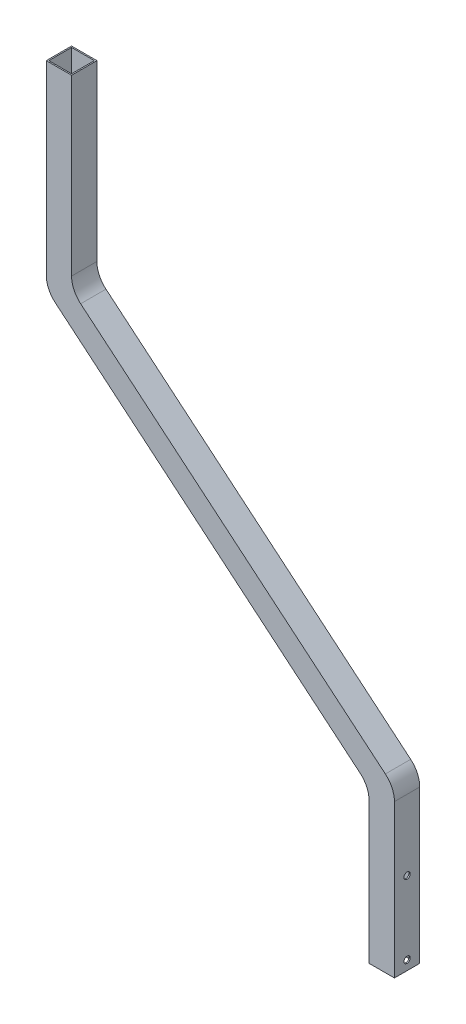
SolidWorks part; units mm, degrees
material "Alloy Steel"
ref_plane "Front Plane" through (0, 0, 0) normal (0, 0, 1) x (1, 0, 0)
ref_plane "Top Plane" through (0, 0, 0) normal (0, 1, 0) x (1, 0, 0)
ref_plane "Right Plane" through (0, 0, 0) normal (1, 0, 0) x (0, 0, -1)
sketch "Sketch1" plane through (0, 0, 0) normal (0, 0, 1) x (1, 0, 0)
  line L0 (0, 0) -> (-698.5, 0) construction
  line L1 (0, 0) -> (0, 1244.6) construction
  line L21 (0, 0) -> (0, 330.2)
  line L22 (0, 330.2) -> (-647.7, 871.9127)
  line L23 (-647.7, 1244.6) -> (-698.5, 1244.6)
  line L24 (-50.8, 0) -> (-50.8, 306.4618)
  line L25 (-50.8, 306.4618) -> (-698.5, 848.1746)
  line L26 (-50.8, 306.4618) -> (-749.3, 890.6618) construction
  line L27 (-647.7, 871.9127) -> (-647.7, 1244.6)
  line L28 (-698.5, 848.1746) -> (-698.5, 1244.6)
  line L29 (-749.3, 890.6618) -> (-749.3, 1244.6) construction
  line L30 (-50.8, 0) -> (0, 0)
  line L31 (-698.5, 914.4) -> (-698.5, 1244.6) construction
  line L32 (0, 330.2) -> (-698.5, 914.4) construction
  dimension "D1" = 698.5
  dimension "D2" = 1244.6
  dimension "D3" = 330.2
  dimension "D4" = 50.8
  dimension "D5" = 50.8
extrude "Boss-Extrude1" add sketch "Sketch1" along normal blind 50.8
fillet "Fillet1" radius 50.8 4 edges at (-50.8, 306.4618, 25.4) (0, 330.2, 25.4) (-647.7, 871.9127, 25.4) (-698.5, 848.1746, 25.4)
shell "Shell1" thickness 2.54
sketch "Sketch2" plane through (0, 0, 0) normal (0, -1, 0) x (1, 0, 0)
  line L0 (-2.54, 48.26) -> (-48.26, 48.26)
  line L5 (-48.26, 2.54) -> (-48.26, 48.26)
  line L6 (-2.54, 2.54) -> (-48.26, 2.54)
  line L7 (-2.54, 2.54) -> (-2.54, 48.26)
extrude "Cut-Extrude1" cut sketch "Sketch2" against normal blind 50.8
hole_wizard "#97 (0.5) Diameter Hole1" positions "3DSketch1" profile "Sketch3" hole size "#97" standard "ANSI Inch" end condition through all
sketch3d "3DSketch1"
  line L0 (0, 0, 50.8) -> (0, 306.4618, 50.8) construction
  line L1 (0, 0, 50.8) -> (0, 0, 0) construction
  point P0 (0, 19.05, 25.4)
  point P2 (0, 165.1, 25.4)
  dimension "D1" = 25.4
  dimension "D2" = 25.4
  dimension "D3" = 19.05
  dimension "D4" = 146.05
sketch "Sketch3" plane through (0, 19.05, 25.4) normal (0, 1, 0) x (0, 0, -1)
  line L0 (0, 0) -> (0, 698.5)
  line L1 (0, 698.5) -> (6.35, 698.5)
  line L2 (6.35, 698.5) -> (6.35, 0)
  line L5 (6.35, 0) -> (0, 0)
  line L11 (0, -6.35) -> (0, 107.95) construction
  dimension "Thru Hole Dia." = 12.7
  dimension "Thru Hole Depth" = 698.5
hole_wizard "#97 (0.5) Diameter Hole2" positions "3DSketch2" profile "Sketch4" hole size "#97" standard "ANSI Inch"
sketch3d "3DSketch2"
  line L0 (-680.291, 832.9452, 50.8) -> (-680.291, 832.9452, 0) construction
  line L1 (-680.291, 832.9452, 50.8) -> (-69.009, 321.6912, 50.8) construction
  point P0 (-582.8722, 751.4677, 25.4)
  dimension "D1" = 127
  dimension "D2" = 25.4
sketch "Sketch4" plane through (-582.8722, 751.4677, 25.4) normal (0, 0, 1) x (0.7671, -0.6416, 0)
  line L0 (0, 0) -> (0, 16.5155)
  line L1 (0, 16.5155) -> (6.35, 12.7)
  line L2 (6.35, 12.7) -> (6.35, 0)
  line L5 (6.35, 0) -> (0, 0)
  line L10 (0, 16.5155) -> (-6.35, 12.7) construction
  line L11 (0, -6.35) -> (0, 107.95) construction
  dimension "Hole Dia." = 12.7
  dimension "Hole Depth" = 12.7
  dimension "Drill Angle" = 118
